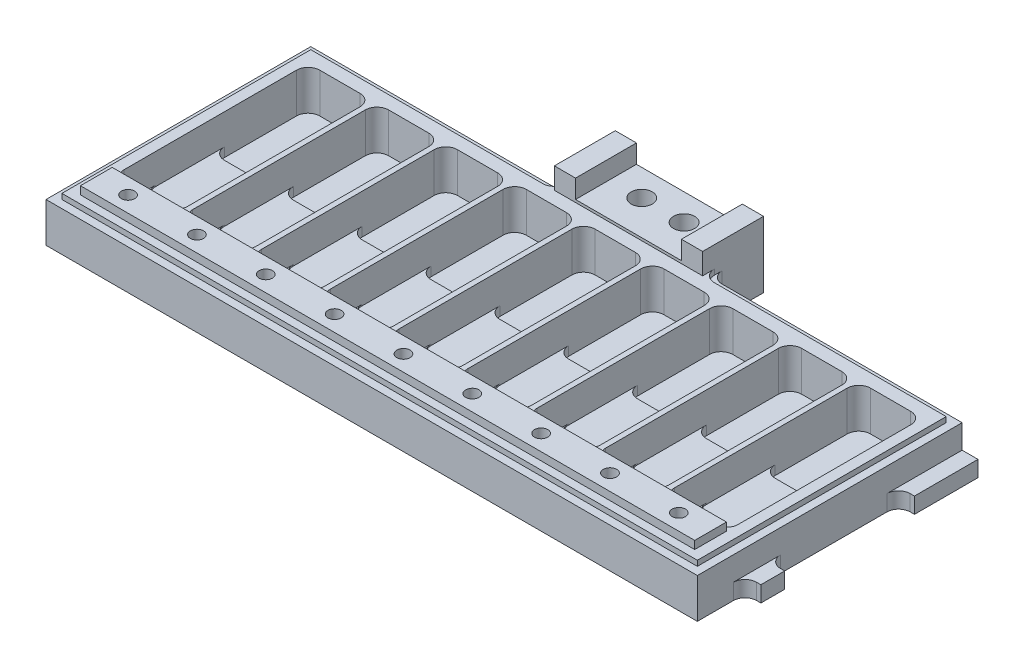
SolidWorks part; units mm, degrees
material "AISI 316"
ref_plane "Front Plane" through (0, 0, 0) normal (0, 0, 1) x (1, 0, 0)
ref_plane "Top Plane" through (0, 0, 0) normal (0, 1, 0) x (1, 0, 0)
ref_plane "Right Plane" through (0, 0, 0) normal (1, 0, 0) x (0, 0, -1)
sketch "Sketch1" plane through (0, 0, 0) normal (0, 1, 0) x (1, 0, 0)
  line L1 (0, 0) -> (123, 0)
  line L2 (0, 0) -> (0, 50)
  line L3 (0, 50) -> (123, 50)
  line L4 (123, 0) -> (123, 50)
  dimension "D1" = 123
  dimension "D2" = 50
extrude "Boss-Extrude1" add sketch "Sketch1" along normal blind 8.5 contours L1 L4 L3 L2
sketch "Sketch2" plane through (0, 8.5, 0) normal (0, 1, 0) x (1, 0, 0)
  line L0 (0, 0) -> (0, 50) construction
  line L1 (3.5, 46) -> (15.5, 46)
  line L2 (3.5, 46) -> (3.5, 9)
  line L3 (3.5, 9) -> (15.5, 9)
  line L4 (15.5, 46) -> (15.5, 9)
  line L8 (0, 50) -> (123, 50) construction
  dimension "D1" = 3.5
  dimension "D2" = 4
  dimension "D3" = 37
  dimension "D4" = 12
extrude "Cut-Extrude1" cut sketch "Sketch2" against normal blind 7.5 contours L2 L3 L4 L1
sketch "Sketch3" plane through (0, 1, 0) normal (0, 1, 0) x (1, 0, 0)
  line L0 (3.5, 46) -> (3.5, 9) construction
  line L1 (3.5, 28) -> (15.5, 28)
  line L2 (3.5, 28) -> (3.5, 15)
  line L3 (3.5, 15) -> (15.5, 15)
  line L4 (15.5, 28) -> (15.5, 15)
  line L5 (15.5, 46) -> (15.5, 9) construction
  line L6 (3.5, 9) -> (15.5, 9) construction
  line L7 (3.5, 46) -> (15.5, 46) construction
  dimension "D1" = 6
  dimension "D2" = 18
extrude "Boss-Extrude2" add sketch "Sketch3" along normal blind 1.75
fillet "Fillet1" radius 2.2 4 edges at (3.5, 1.875, -28) (15.5, 1.875, -28) (3.5, 4.75, -46) (15.5, 4.75, -46)
sketch "Sketch12" plane through (3.5, 0, 0) normal (1, 0, 0) x (0, 0, -1)
  line L1 (9, 10) -> (3, 10)
  line L2 (9, 10) -> (9, 8.5)
  line L3 (9, 8.5) -> (3, 8.5)
  line L4 (3, 10) -> (3, 8.5)
  line L5 (50, 8.5) -> (50, 0) construction
  dimension "D1" = 41
  dimension "D2" = 6
  dimension "D3" = 1.5
extrude "Boss-Extrude8" add sketch "Sketch12" along normal blind 116
sketch "Sketch10" plane through (15.5, 0, 0) normal (-1, 0, 0) x (0, 0, 1)
  line L0 (-15, 2.75) -> (-15, 1) construction
  line L1 (-15, 1) -> (-9, 1)
  line L2 (-15, 1) -> (-15, 3)
  line L3 (-15, 3) -> (-12.875, 3) construction
  line L4 (-9, 1) -> (-9, 3)
  line L5 (-15, 1) -> (-9, 1) construction
  line L6 (-9, 1) -> (-9, 8.5) construction
  line L7 (-12.875, 3) -> (-12.125, 3) construction
  line L8 (-12.125, 3) -> (-9, 3) construction
  line L9 (-12.875, 3) -> (-12.125, 3) construction
  line L10 (-15, 3) -> (-9, 3)
  arc A0 (-12.125, 3) -> (-12.875, 3) centre (-12.5, 3) ccw construction
  arc A1 (-12.875, 3) -> (-12.125, 3) centre (-12.5, 3) ccw construction
  dimension "D2" = 0.75
  dimension "D1" = 2
  dimension "D3" = 2.5
extrude "Boss-Extrude7" add sketch "Sketch10" along normal up to next contours L1 L4 L10 L2
fillet "Fillet2" radius 2.2 4 edges at (3.5, 5.75, -9) (15.5, 5.75, -9) (3.5, 2.875, -15) (15.5, 2.875, -15)
chamfer "Chamfer2" [suppressed] distance 1 angle 14
fillet "Fillet3" [suppressed] radius 0.5
pattern_linear "LPattern1" count 9 spacing 13 along (1, 0, 0) of "Cut-Extrude1", "Fillet1", "Boss-Extrude2", "Fillet2", "Boss-Extrude7", "Chamfer2", "Fillet3"
sketch "Sketch4" plane through (0, 0, -50) normal (0, 0, -1) x (-1, 0, 0)
  line L0 (0, 8.5) -> (-123, 8.5) construction
  line L2 (-75.5, 0) -> (-75.5, 12.5)
  line L3 (-75.5, 12.5) -> (-71.5, 12.5)
  line L4 (-47.5, 0) -> (-47.5, 12.5)
  line L5 (-51.5, 12.5) -> (-47.5, 12.5)
  line L7 (-71.5, 12.5) -> (-71.5, 8.5)
  line L8 (-71.5, 8.5) -> (-51.5, 8.5)
  line L9 (-51.5, 12.5) -> (-51.5, 8.5)
  line L10 (0, 0) -> (-123, 0) construction
  line L11 (-75.5, 0) -> (-47.5, 0)
  point P13 (-61.5, 8.5)
  point P14 (-61.5, 0)
  dimension "D1" = 20
  dimension "D2" = 4
  dimension "D3" = 4
  dimension "D5" = 4
  dimension "D6" = 0
extrude "Boss-Extrude3" add sketch "Sketch4" along normal blind 10
sketch "Sketch5" plane through (0, 8.5, 0) normal (0, 1, 0) x (1, 0, 0)
  line L0 (47.5, 60) -> (47.5, 50) construction
  line L1 (75.5, 60) -> (75.5, 50) construction
  line L2 (75.5, 50) -> (123, 50) construction
  line L3 (47.5, 50) -> (51.5, 50) construction
  circle A0 centre (57.5, 55) radius 2
  circle A1 centre (65.5, 55) radius 2
  dimension "D1" = 4
  dimension "D2" = 4
  dimension "D3" = 10
  dimension "D4" = 10
  dimension "D5" = 5
  dimension "D6" = 5
extrude "Cut-Extrude2" cut sketch "Sketch5" against normal through all
sketch "Sketch6" plane through (0, 8.5, 0) normal (0, 1, 0) x (1, 0, 0)
  line L2 (75.5, 50) -> (123, 50) construction
  line L3 (123, 0) -> (123, 50) construction
  line L4 (0, 0) -> (123, 0) construction
  line L5 (0, 0) -> (0, 50) construction
  line L7 (0, 50) -> (47.5, 50)
  line L9 (75.5, 50) -> (123, 50)
  line L10 (123, 0) -> (123, 50)
  line L11 (0, 0) -> (123, 0)
  line L12 (0, 0) -> (0, 50)
  line L14 (75.5, 48.5) -> (47.5, 48.5) construction
  line L17 (47.5, 50) -> (51.5, 50) construction
  line L26 (47.5, 50) -> (47.5, 48.5)
  line L28 (75.5, 50) -> (75.5, 48.5)
  line L31 (75.5, 48.5) -> (70, 48.5)
  line L33 (70, 48.5) -> (70, 58.5)
  line L34 (1.5, 48.5) -> (1.5, 1.5)
  line L35 (1.5, 1.5) -> (121.5, 1.5)
  line L36 (121.5, 1.5) -> (121.5, 48.5)
  line L37 (121.5, 48.5) -> (75.5, 48.5)
  line L38 (70, 58.5) -> (53, 58.5)
  line L39 (53, 58.5) -> (53, 48.5)
  line L40 (53, 48.5) -> (47.5, 48.5)
  line L43 (47.5, 48.5) -> (1.5, 48.5)
  line L44 (1.5, 48.5) -> (1.5, 1.5)
  line L45 (1.5, 1.5) -> (121.5, 1.5)
  line L46 (121.5, 1.5) -> (121.5, 48.5)
  line L47 (121.5, 48.5) -> (75.5, 48.5)
  line L53 (47.5, 48.5) -> (1.5, 48.5)
  dimension "D1" = 1.5
extrude "Cut-Extrude3" cut sketch "Sketch6" against normal blind 1
sketch "Sketch7" plane through (0, 7.5, 0) normal (0, 1, 0) x (1, 0, 0)
  line L0 (1.5, 48.5) -> (47.5, 48.5) construction
  line L1 (51.5, 50) -> (47.5, 50)
  line L2 (51.5, 50) -> (51.5, 48.5)
  line L3 (51.5, 48.5) -> (47.5, 48.5)
  line L4 (47.5, 50) -> (47.5, 48.5)
  line L5 (47.5, 60) -> (47.5, 50) construction
  line L6 (75.5, 50) -> (71.5, 50)
  line L7 (75.5, 50) -> (75.5, 48.5)
  line L8 (75.5, 48.5) -> (71.5, 48.5)
  line L9 (71.5, 50) -> (71.5, 48.5)
  line L10 (47.5, 50) -> (51.5, 50) construction
extrude "Boss-Extrude4" add sketch "Sketch7" along normal up to surface (5 mm away) up to face at (49.5, 12.5, -55)
sketch "Sketch8" plane through (0, 0, 0) normal (-1, 0, 0) x (0, 0, 1)
  line L0 (0, 0) -> (-50, 0) construction
  line L1 (-50, 0) -> (-38, 0)
  line L2 (-50, 0) -> (-50, 3)
  line L3 (-50, 3) -> (-38, 3)
  line L4 (-38, 0) -> (-38, 3)
  line L5 (-9, 0) -> (-13.5, 0)
  line L6 (-9, 0) -> (-9, 3)
  line L7 (-9, 3) -> (-13.5, 3)
  line L8 (-13.5, 0) -> (-13.5, 3)
  dimension "D1" = 12
  dimension "D2" = 4.5
  dimension "D3" = 9
  dimension "D4" = 3
  dimension "D5" = 3
extrude "Boss-Extrude5" add sketch "Sketch8" along normal blind 3
ref_plane "Plane1" through (61.5, 0, 0) normal (-1, 0, 0) x (0, 0, 1)
mirror "Mirror1" about plane through (61.5, 0, 0) normal (-1, 0, 0) of "Boss-Extrude5"
hole_wizard "M3 Tapped Hole1" positions "Sketch13" profile "Sketch15" tap size "M3" standard "ISO" end condition through all
sketch "Sketch13" plane through (0, 10, 0) normal (0, 1, 0) x (1, 0, 0)
  point P0 (9.5, 6)
  point P3 (22.5, 6)
  point P5 (35.5, 6)
  point P7 (48.5, 6)
  point P9 (61.5, 6)
  point P11 (74.5, 6)
  point P13 (87.5, 6)
  point P15 (100.5, 6)
  point P17 (113.5, 6)
sketch "Sketch15" plane through (9.5, 10, -6) normal (1, 0, 0) x (0, 0, 1)
  line L0 (0, 0) -> (0, 10)
  line L1 (0, 10) -> (1.25, 10)
  line L2 (1.25, 10) -> (1.25, 0)
  line L5 (1.25, 0) -> (0, 0)
  line L11 (0, -6.35) -> (0, 107.95) construction
  dimension "Thru Tap Drill Dia." = 2.5
  dimension "Thru Tap Drill Depth" = 10
thread "Thread1" [suppressed] pitch 0.5 start angle 0, offset 0, length 0, pitch 0.5, diameter 2.5
ref_plane "Plane2" through (8.25, 10, -6) normal (0, 0, 1) x (-1, 0, 0)
sketch "Thread Profile1" plane through (8.25, 10, -6) normal (0, 0, 1) x (-1, 0, 0)
  line L0 (0, 0) -> (0, 0.5) construction
  line L1 (0, 0) -> (0.2706, 0.1562)
  line L2 (0.2706, 0.1562) -> (0.2706, 0.2187)
  line L3 (0.2706, 0.2187) -> (0, 0.375)
  line L4 (0.2706, 0.1875) -> (0, 0.1875) construction
  line L11 (0, 0) -> (0, 0.375)
  point P2 (0, 0)
  dimension "Pitch" = 0.5
  dimension "Profile_Angle" = 60
  dimension "Profile_Land" = 0.0625
  dimension "Profile_Height" = 0.2706
pattern_linear "LPattern2" [suppressed] count 9 spacing 13
sketch "Sketch16" plane through (0, 8.5, 0) normal (0, 1, 0) x (1, 0, 0)
  line L1 (51.5, 60) -> (71.5, 60)
  line L2 (51.5, 60) -> (51.5, 48.5)
  line L3 (51.5, 48.5) -> (71.5, 48.5)
  line L4 (71.5, 60) -> (71.5, 48.5)
  circle A0 centre (65.5, 55) radius 2 construction
  circle A1 centre (57.5, 55) radius 2 construction
  circle A2 centre (65.5, 55) radius 2
  circle A3 centre (57.5, 55) radius 2
extrude "Boss-Extrude9" add sketch "Sketch16" along normal blind 0.5
fillet "Fillet4" radius 2.2 8 edges at (75.5, 3.75, -50) (123, 1.5, -38) (123, 1.5, -13.5) (123, 1.5, -9) (0, 1.5, -9) (0, 1.5, -38) (0, 1.5, -13.5) (47.5, 3.75, -50)
fillet "Fillet5" radius 2.2 2 edges at (47.5, 8, -48.5) (75.5, 8, -48.5)
ref_plane "Plane3" through (61.5, 0, 0) normal (1, 0, 0) x (0, 0, -1)
